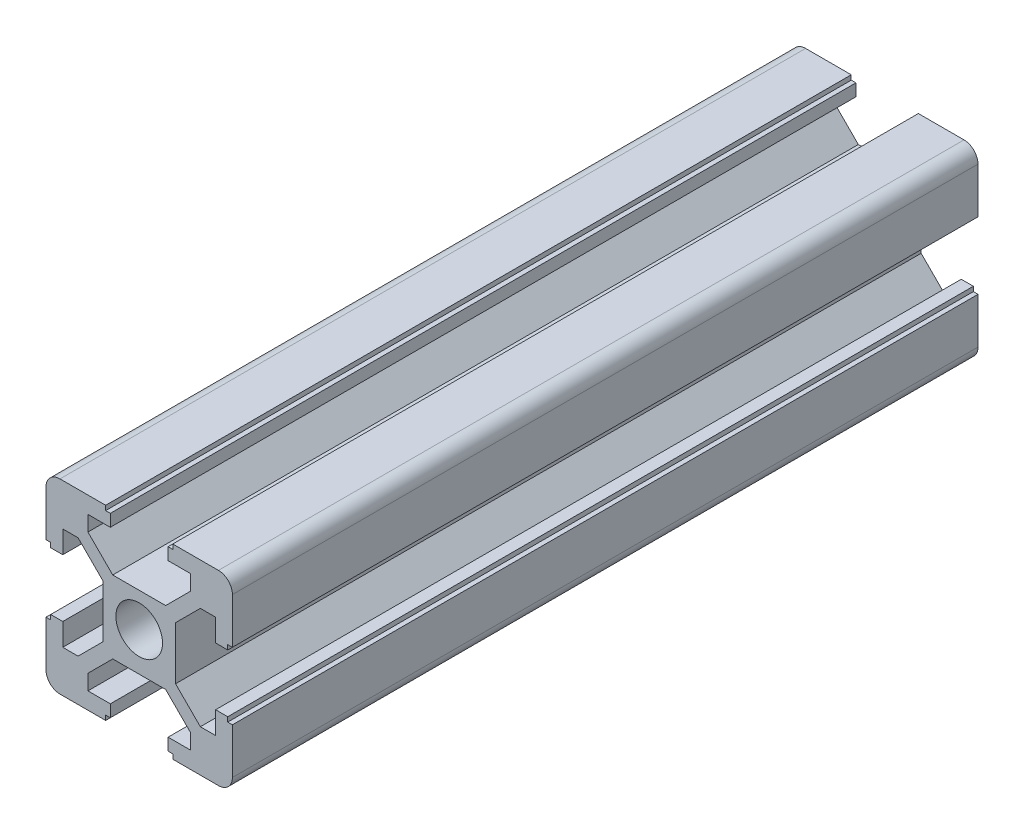
SolidWorks part; units mm, degrees
ref_plane "Front Plane" through (0, 0, 0) normal (0, 0, 1) x (1, 0, 0)
ref_plane "Top Plane" through (0, 0, 0) normal (0, 1, 0) x (1, 0, 0)
ref_plane "Right Plane" through (0, 0, 0) normal (1, 0, 0) x (0, 0, -1)
sketch "Sketch1" plane through (0, 0, 0) normal (0, 0, 1) x (1, 0, 0)
  line L0 (0, 13.3843) -> (0, -12.9126) construction
  line L1 (-14.4653, 0) -> (14.4653, 0) construction
  line L2 (2.8393, 3.9) -> (5.5, 6.5607)
  line L3 (-8.5, 10) -> (-3.6, 10)
  line L4 (-10, 8.5) -> (-10, 3.6)
  line L5 (-8.5, -10) -> (-3.6, -10)
  line L6 (10, 8.5) -> (10, 3.6)
  line L7 (-10, 10) -> (10, -10) construction
  line L8 (-10, -10) -> (10, 10) construction
  line L9 (-5.5, 8.2) -> (-3.1, 8.2)
  line L10 (-5.9626, 4.902) -> (-4.902, 5.9626) construction
  line L11 (-2.8393, 3.9) -> (-5.5, 6.5607)
  line L12 (-5.5, 8.2) -> (-5.5, 6.5607)
  line L13 (-2.8393, 3.9) -> (2.8393, 3.9)
  line L14 (5.5, 8.2) -> (5.5, 6.5607)
  line L15 (-3.1, 9.5) -> (-3.1, 8.2)
  line L16 (3.1, 9.5) -> (3.1, 8.2)
  line L17 (-3.1, 9.5) -> (3.1, 9.5) construction
  line L18 (-3.1, 9.5) -> (-3.6, 9.5)
  line L19 (-3.6, 9.5) -> (-3.6, 10)
  line L20 (3.1, 9.5) -> (3.6, 9.5)
  line L21 (3.6, 9.5) -> (3.6, 10)
  line L22 (3.6, 10) -> (8.5, 10)
  line L23 (3.1, 8.2) -> (5.5, 8.2)
  line L24 (-9.5, -3.1) -> (-9.5, -3.6)
  line L25 (-9.5, -3.6) -> (-10, -3.6)
  line L26 (-9.5, -3.1) -> (-8.2, -3.1)
  line L27 (-8.2, -3.1) -> (-8.2, -5.5)
  line L28 (-8.2, -5.5) -> (-6.5607, -5.5)
  line L29 (-3.9, -2.8393) -> (-6.5607, -5.5)
  line L30 (-3.9, 2.8393) -> (-3.9, -2.8393)
  line L31 (-3.9, 2.8393) -> (-6.5607, 5.5)
  line L32 (-8.2, 5.5) -> (-6.5607, 5.5)
  line L33 (-8.2, 5.5) -> (-8.2, 3.1)
  line L34 (-9.5, 3.1) -> (-8.2, 3.1)
  line L35 (-9.5, 3.1) -> (-9.5, 3.6)
  line L36 (-9.5, 3.6) -> (-10, 3.6)
  line L37 (-3.6, -9.5) -> (-3.6, -10)
  line L38 (-3.1, -9.5) -> (-3.6, -9.5)
  line L39 (-3.1, -9.5) -> (-3.1, -8.2)
  line L40 (-3.1, -8.2) -> (-5.5, -8.2)
  line L41 (-5.5, -8.2) -> (-5.5, -6.5607)
  line L42 (-2.8393, -3.9) -> (-5.5, -6.5607)
  line L43 (2.8393, -3.9) -> (-2.8393, -3.9)
  line L44 (2.8393, -3.9) -> (5.5, -6.5607)
  line L45 (5.5, -8.2) -> (5.5, -6.5607)
  line L46 (5.5, -8.2) -> (3.1, -8.2)
  line L47 (3.1, -9.5) -> (3.6, -9.5)
  line L48 (3.1, -9.5) -> (3.1, -8.2)
  line L49 (3.6, -9.5) -> (3.6, -10)
  line L50 (9.5, -3.6) -> (10, -3.6)
  line L51 (9.5, -3.1) -> (9.5, -3.6)
  line L52 (9.5, -3.1) -> (8.2, -3.1)
  line L53 (8.2, -5.5) -> (8.2, -3.1)
  line L54 (8.2, -5.5) -> (6.5607, -5.5)
  line L55 (3.9, -2.8393) -> (6.5607, -5.5)
  line L56 (3.9, -2.8393) -> (3.9, 2.8393)
  line L57 (3.9, 2.8393) -> (6.5607, 5.5)
  line L58 (8.2, 5.5) -> (6.5607, 5.5)
  line L59 (8.2, 3.1) -> (8.2, 5.5)
  line L60 (9.5, 3.1) -> (8.2, 3.1)
  line L61 (9.5, 3.1) -> (9.5, 3.6)
  line L62 (9.5, 3.6) -> (10, 3.6)
  line L63 (-10, -3.6) -> (-10, -8.5)
  line L64 (3.6, -10) -> (8.5, -10)
  line L65 (10, -3.6) -> (10, -8.5)
  arc A0 (8.5, 10) -> (10, 8.5) centre (8.5, 8.5) cw
  arc A1 (8.5, -10) -> (10, -8.5) centre (8.5, -8.5) ccw
  arc A2 (-10, -8.5) -> (-8.5, -10) centre (-8.5, -8.5) ccw
  arc A3 (-8.5, 10) -> (-10, 8.5) centre (-8.5, 8.5) ccw
  circle A4 centre (0, 0.2358) radius 2.5
  point P5 (0, 0)
  point P30 (-5.4323, 5.4323)
  point P38 (0, 9.5)
  dimension "D3" = 1.5
  dimension "D15" = 5
  dimension "D1" = 20
  dimension "D2" = 20
  dimension "D4" = 6.2
  dimension "D5" = 11
  dimension "D6" = 1.8
  dimension "D7" = 1.5
  dimension "D8" = 90
  dimension "D9" = 0.5
  dimension "D10" = 0.5
  dimension "D11" = 0.5
  dimension "D12" = 0.5
  dimension "D13" = 6.1
  dimension "D14" = 45
extrude "Boss-Extrude1" add sketch "Sketch1" along normal blind 80
